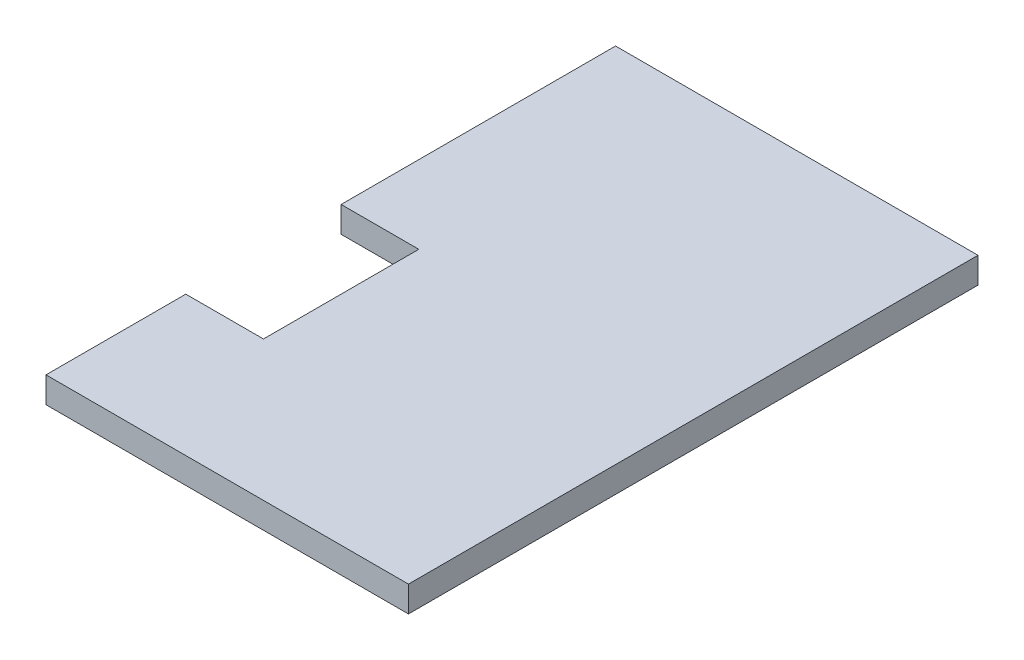
SolidWorks part; units mm, degrees
ref_plane "Alzado" through (0, 0, 0) normal (0, 0, 1) x (1, 0, 0)
ref_plane "Planta" through (0, 0, 0) normal (0, 1, 0) x (1, 0, 0)
ref_plane "Vista lateral" through (0, 0, 0) normal (1, 0, 0) x (0, 0, -1)
sketch "Croquis1" plane through (0, 0, 0) normal (0, 1, 0) x (1, 0, 0)
  line L1 (-15.9206, 27.9242) -> (54.0794, 27.9242)
  line L2 (-15.9206, 27.9242) -> (-15.9206, -82.0758)
  line L3 (-15.9206, -82.0758) -> (54.0794, -82.0758)
  line L4 (54.0794, 27.9242) -> (54.0794, -82.0758)
  dimension "D1" = 70
  dimension "D2" = 110
extrude "Saliente-Extruir1" add sketch "Croquis1" along normal blind 5
sketch "Croquis2" plane through (0, 5, 0) normal (0, 1, 0) x (1, 0, 0)
  line L0 (-15.9206, -25.0758) -> (-0.9206, -25.0758)
  line L1 (-15.9206, 27.9242) -> (-15.9206, -82.0758) construction
  line L2 (-0.9206, -25.0758) -> (-0.9206, -55.0758)
  line L3 (-0.9206, -55.0758) -> (-15.9206, -55.0758)
  line L4 (-15.9206, -82.0758) -> (54.0794, -82.0758) construction
  line L5 (-15.9206, -25.0758) -> (-15.9206, -55.0758)
  dimension "D1" = 27
  dimension "D2" = 30
  dimension "D3" = 15
extrude "Cortar-Extruir1" cut sketch "Croquis2" against normal through all
